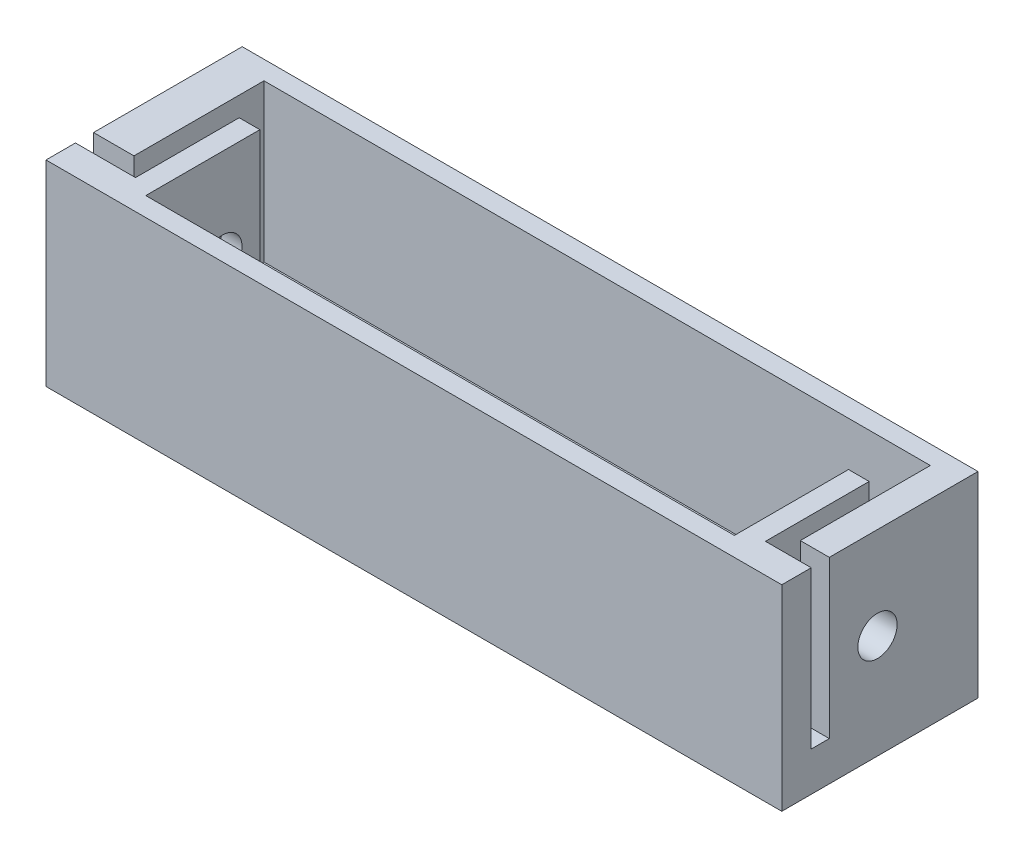
SolidWorks part; units mm, degrees
ref_plane "Front Plane" through (0, 0, 0) normal (0, 0, 1) x (1, 0, 0)
ref_plane "Top Plane" through (0, 0, 0) normal (0, 1, 0) x (1, 0, 0)
ref_plane "Right Plane" through (0, 0, 0) normal (1, 0, 0) x (0, 0, -1)
sketch "Sketch1" plane through (0, 0, 0) normal (0, 0, 1) x (1, 0, 0)
  line L1 (-38.2269, 31.9273) -> (36.7731, 31.9273)
  line L2 (-38.2269, 31.9273) -> (-38.2269, 11.9273)
  line L3 (-38.2269, 11.9273) -> (36.7731, 11.9273)
  line L4 (36.7731, 31.9273) -> (36.7731, 11.9273)
  dimension "D1" = 75
  dimension "D2" = 20
extrude "Boss-Extrude1" add sketch "Sketch1" along normal blind 20
sketch "Sketch2" plane through (0, 31.9273, 0) normal (0, 1, 0) x (1, 0, 0)
  line L0 (42.8027, -15.156) -> (42.499, -16.9973)
  line L5 (30, -6.4275) -> (30, -18.0596)
  line L14 (-34.1058, -4.3768) -> (-34.1058, -1.9022)
  line L17 (-34.1058, -1.9022) -> (-32.1058, -1.9022)
  line L26 (-32.1058, -1.9022) -> (32.1058, -1.9022)
  line L28 (-30, -18.0596) -> (30, -18.0596)
  line L29 (33.8147, -4.3768) -> (33.8147, -15.156)
  line L30 (32.1058, -1.9022) -> (33.8147, -1.9022)
  line L31 (33.8147, -1.9022) -> (33.8147, -4.3768)
  line L32 (-34.1058, -4.3768) -> (-34.1058, -15.156)
  line L33 (-34.1058, -15.156) -> (-42.8027, -15.156)
  line L34 (-30, -6.4275) -> (-30, -18.0596)
  line L36 (-30, -6.4275) -> (-32.1058, -6.4275)
  line L37 (-32.1058, -6.4275) -> (-32.1058, -16.9973)
  line L38 (-32.1058, -16.9973) -> (-42.499, -16.9973)
  line L39 (-42.8027, -15.156) -> (-42.499, -16.9973)
  line L40 (30, -18.0596) -> (-30, -18.0596)
  line L41 (34.1058, -15.156) -> (33.8147, -15.156)
  line L42 (32.1058, -16.9973) -> (42.499, -16.9973)
  line L43 (34.1058, -15.156) -> (42.8027, -15.156)
  line L45 (32.1058, -1.9022) -> (-32.1058, -1.9022)
  line L48 (32.1058, -6.4275) -> (32.1058, -16.9973)
  line L49 (30, -6.4275) -> (32.1058, -6.4275)
extrude "Cut-Extrude2" cut sketch "Sketch2" against normal blind 16
sketch "Sketch3" plane through (36.7731, 0, 0) normal (1, 0, 0) x (0, 0, -1)
  circle A0 centre (-10.2457, 22.5371) radius 2
  dimension "D1" = 4
extrude "Cut-Extrude3" cut sketch "Sketch3" against normal blind 96 contours A0
